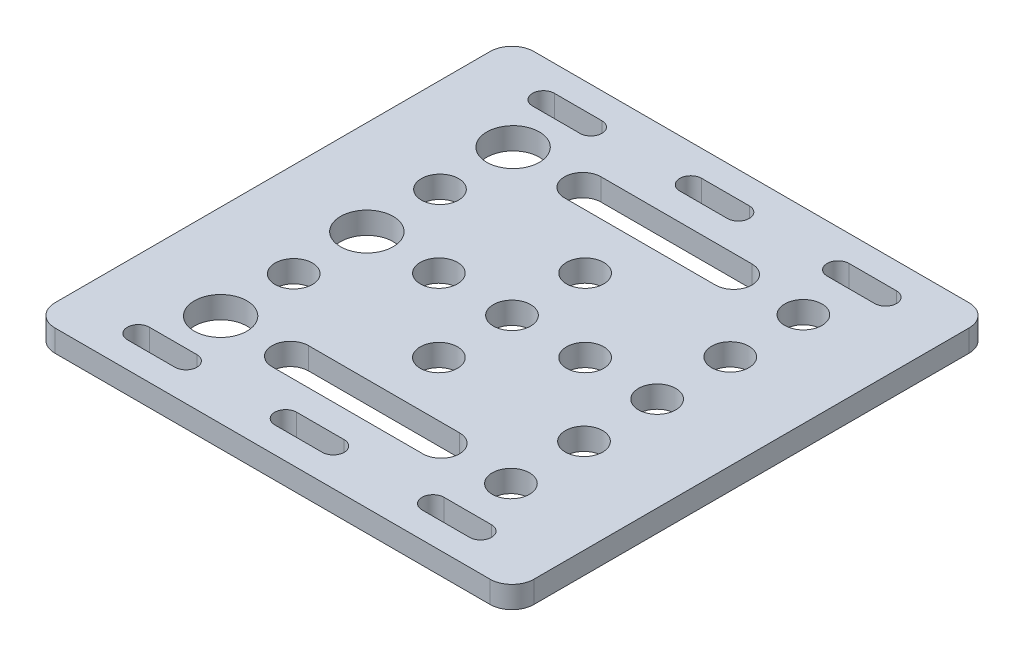
SolidWorks part; units mm, degrees
ref_plane "Front Plane" through (0, 0, 0) normal (0, 0, 1) x (1, 0, 0)
ref_plane "Top Plane" through (0, 0, 0) normal (0, 1, 0) x (1, 0, 0)
ref_plane "Right Plane" through (0, 0, 0) normal (1, 0, 0) x (0, 0, -1)
ref_plane "Plane1" through (0, 0, 0) normal (0, -1, 0) x (1, 0, 0)
sketch "Sketch1" plane through (0, 0, 0) normal (0, -1, 0) x (1, 0, 0)
  line L0 (-10.32, -17.5) -> (10.32, -17.5)
  line L1 (10.32, -22.5) -> (-10.32, -22.5)
  line L2 (-23.4, -26.2) -> (-16.9, -26.2)
  line L3 (-16.9, -29.2) -> (-23.4, -29.2)
  line L4 (-10.32, 22.5) -> (10.32, 22.5)
  line L5 (10.32, 17.5) -> (-10.32, 17.5)
  line L6 (-3.25, 29.2) -> (3.25, 29.2)
  line L7 (3.25, 26.2) -> (-3.25, 26.2)
  line L8 (23.4, 26.2) -> (16.9, 26.2)
  line L9 (16.9, 29.2) -> (23.4, 29.2)
  line L10 (-23.4, 29.2) -> (-16.9, 29.2)
  line L11 (-16.9, 26.2) -> (-23.4, 26.2)
  line L12 (23.4, -29.2) -> (16.9, -29.2)
  line L13 (16.9, -26.2) -> (23.4, -26.2)
  line L14 (-3.25, -26.2) -> (3.25, -26.2)
  line L15 (3.25, -29.2) -> (-3.25, -29.2)
  line L16 (-32.75, 29.75) -> (-32.75, -29.75)
  line L17 (-29.75, -32.75) -> (29.75, -32.75)
  line L18 (32.75, -29.75) -> (32.75, 29.75)
  line L19 (29.75, 32.75) -> (-29.75, 32.75)
  circle A0 centre (0, -10) radius 2.55
  circle A1 centre (-10, 0) radius 2.55
  circle A2 centre (-19.85, 0) radius 3.6
  circle A3 centre (-19.85, -10) radius 2.55
  circle A4 centre (19.85, 0) radius 2.55
  circle A5 centre (0, 10) radius 2.55
  circle A6 centre (19.85, 10) radius 2.55
  arc A7 (10.32, -17.5) -> (10.32, -22.5) centre (10.32, -20) cw
  arc A8 (-10.32, -22.5) -> (-10.32, -17.5) centre (-10.32, -20) cw
  arc A9 (-16.9, -26.2) -> (-16.9, -29.2) centre (-16.9, -27.7) cw
  arc A10 (-23.4, -29.2) -> (-23.4, -26.2) centre (-23.4, -27.7) cw
  arc A11 (10.32, 22.5) -> (10.32, 17.5) centre (10.32, 20) cw
  arc A12 (-10.32, 17.5) -> (-10.32, 22.5) centre (-10.32, 20) cw
  arc A13 (3.25, 29.2) -> (3.25, 26.2) centre (3.25, 27.7) cw
  arc A14 (-3.25, 26.2) -> (-3.25, 29.2) centre (-3.25, 27.7) cw
  arc A15 (16.9, 26.2) -> (16.9, 29.2) centre (16.9, 27.7) cw
  arc A16 (23.4, 29.2) -> (23.4, 26.2) centre (23.4, 27.7) cw
  arc A17 (-16.9, 29.2) -> (-16.9, 26.2) centre (-16.9, 27.7) cw
  arc A18 (-23.4, 26.2) -> (-23.4, 29.2) centre (-23.4, 27.7) cw
  arc A19 (16.9, -29.2) -> (16.9, -26.2) centre (16.9, -27.7) cw
  arc A20 (23.4, -26.2) -> (23.4, -29.2) centre (23.4, -27.7) cw
  arc A21 (3.25, -26.2) -> (3.25, -29.2) centre (3.25, -27.7) cw
  arc A22 (-3.25, -29.2) -> (-3.25, -26.2) centre (-3.25, -27.7) cw
  circle A23 centre (-19.85, 10) radius 2.55
  circle A24 centre (19.85, -10) radius 2.55
  circle A25 centre (19.85, 20) radius 2.55
  circle A26 centre (19.85, -20) radius 2.55
  circle A27 centre (-19.85, 20) radius 3.6
  circle A28 centre (-19.85, -20) radius 3.6
  circle A29 centre (10, 0) radius 2.55
  circle A30 centre (0, 0) radius 2.55
  arc A31 (-29.75, 32.75) -> (-32.75, 29.75) centre (-29.75, 29.75) ccw
  arc A32 (-32.75, -29.75) -> (-29.75, -32.75) centre (-29.75, -29.75) ccw
  arc A33 (29.75, -32.75) -> (32.75, -29.75) centre (29.75, -29.75) ccw
  arc A34 (32.75, 29.75) -> (29.75, 32.75) centre (29.75, 29.75) ccw
extrude "Boss-Extrude1" add sketch "Sketch1" against normal blind 3
